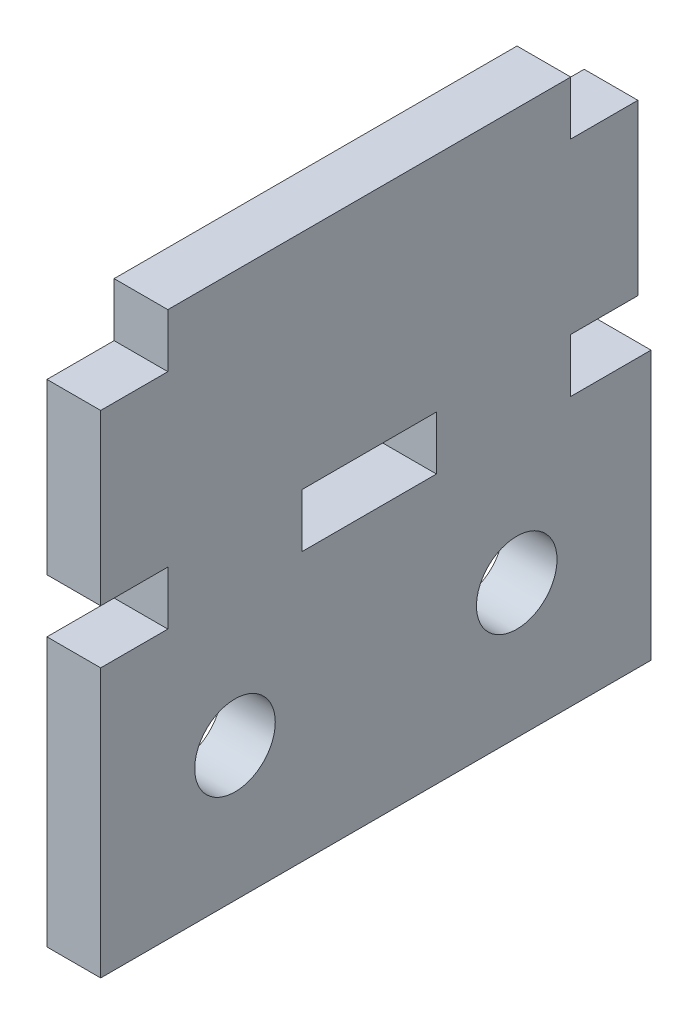
SolidWorks part; units mm, degrees
ref_plane "Front Plane" through (0, 0, 0) normal (0, 0, 1) x (1, 0, 0)
ref_plane "Top Plane" through (0, 0, 0) normal (0, 1, 0) x (1, 0, 0)
ref_plane "Right Plane" through (0, 0, 0) normal (1, 0, 0) x (0, 0, -1)
sketch "Sketch1" plane through (0, 0, 0) normal (1, 0, 0) x (0, 0, -1)
  line L0 (-7.5, 3.15) -> (-7.5, 5.15)
  line L1 (-10, 3.15) -> (-7.5, 3.15)
  line L2 (-10, 3.15) -> (-10, -3.15)
  line L3 (-10, -3.15) -> (-7.5, -3.15)
  line L4 (10, 3.15) -> (10, -3.15)
  line L5 (-10, 3.15) -> (10, -3.15) construction
  line L6 (-10, -3.15) -> (10, 3.15) construction
  line L7 (-7.5, 5.15) -> (-2.5, 5.15)
  line L8 (-2.5, 5.15) -> (-2.5, 3.15)
  line L9 (2.5, 3.15) -> (2.5, 5.15)
  line L10 (2.5, 5.15) -> (7.5, 5.15)
  line L11 (7.5, 5.15) -> (7.5, 3.15)
  line L12 (-2.5, 3.15) -> (2.5, 3.15)
  line L13 (7.5, 3.15) -> (10, 3.15)
  line L14 (-7.5, -3.15) -> (-7.5, -5.15)
  line L15 (-7.5, -5.15) -> (-2.5, -5.15)
  line L16 (-2.5, -5.15) -> (-2.5, -3.15)
  line L17 (7.5, -3.15) -> (7.5, -5.15)
  line L18 (7.5, -5.15) -> (2.5, -5.15)
  line L19 (2.5, -5.15) -> (2.5, -3.15)
  line L20 (-2.5, -3.15) -> (2.5, -3.15)
  line L21 (7.5, -3.15) -> (10, -3.15)
  point P0 (0, 0)
  point P12 (-5, 5.15)
  point P15 (5, 5.15)
  dimension "D1" = 6.3
  dimension "D2" = 20
  dimension "D3" = 5
  dimension "D4" = 2
  dimension "D5" = 5
  dimension "D6" = 5
  dimension "D7" = 2
  dimension "D8" = 5
  dimension "D9" = 2
  dimension "D10" = 2
extrude "Boss-Extrude1" add sketch "Sketch1" along normal blind 2
sketch "Sketch2" plane through (2, 0, 0) normal (1, 0, 0) x (0, 0, -1)
  line L0 (-10, -5.15) -> (-10, -15.15)
  line L1 (-10, -15.15) -> (10.4894, -15.15)
  line L2 (10.4894, -15.15) -> (10.4894, -5.15)
  line L3 (-13.9803, -10.15) -> (16.2549, -10.15) construction
  line L4 (-7.5, -5.15) -> (10.4894, -5.15)
  line L5 (-7.5, -5.15) -> (-10, -5.15)
  circle A0 centre (-5, -10.15) radius 1.5
  circle A1 centre (5.4894, -10.15) radius 1.5
  dimension "D3" = 3
  dimension "D4" = 3
  dimension "D1" = 10
  dimension "D2" = 5
  dimension "D5" = 5
  dimension "D6" = 5
extrude "Boss-Extrude2" add sketch "Sketch2" against normal blind 2
sketch "Sketch3" plane through (2, 0, 0) normal (1, 0, 0) x (0, 0, -1)
  line L0 (-2.5, 5.15) -> (-2.5, 3.15)
  line L1 (-2.5, 3.15) -> (2.5, 3.15)
  line L2 (2.5, 3.15) -> (2.5, 5.15)
  line L3 (2.5, 5.15) -> (-2.5, 5.15)
extrude "Boss-Extrude3" add sketch "Sketch3" against normal blind 2
